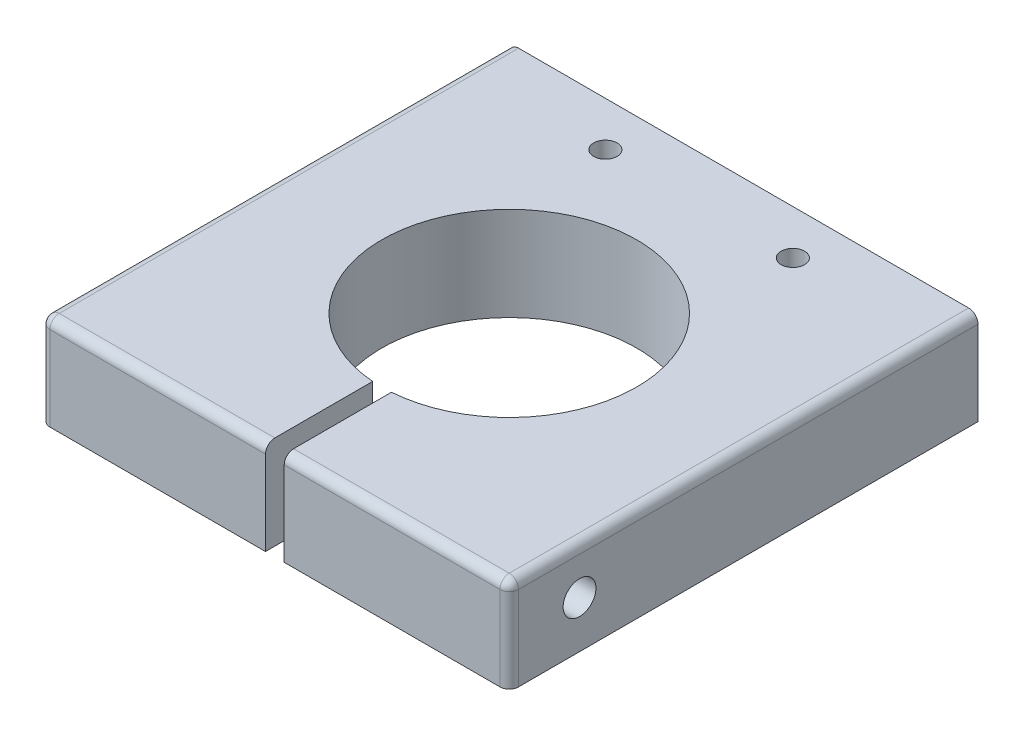
SolidWorks part; units mm, degrees
ref_plane "Front Plane" through (0, 0, 0) normal (0, 0, 1) x (1, 0, 0)
ref_plane "Top Plane" through (0, 0, 0) normal (0, 1, 0) x (1, 0, 0)
ref_plane "Right Plane" through (0, 0, 0) normal (1, 0, 0) x (0, 0, -1)
sketch "Esquisse1" plane through (0, 0, 0) normal (0, 1, 0) x (1, 0, 0)
  line L0 (0, 0) -> (50, 0)
  line L1 (50, 0) -> (50, -100)
  line L2 (50, -100) -> (2, -100)
  line L3 (2, -100) -> (2, -50)
  line L4 (2, -50) -> (0, -50)
  line L5 (0, -50) -> (0, 0)
  line L6 (0, 5.5872) -> (0, -102.666) construction
  dimension "D1" = 50
  dimension "D2" = 100
  dimension "D3" = 48
  dimension "D4" = 50
extrude "Boss.-Extru.1" add sketch "Esquisse1" along normal blind 20
mirror "Symétrie1" about plane through (0, 0, 0) normal (1, 0, 0) of "Boss.-Extru.1"
sketch "Esquisse2" plane through (0, 20, 0) normal (0, 1, 0) x (1, 0, 0)
  line L0 (-2, -50) -> (2, -50) construction
  circle A0 centre (0, -50) radius 27.2
extrude "Enlèv. mat.-Extru.1" cut sketch "Esquisse2" against normal blind 20
sketch "Esquisse3" plane through (0, 20, 0) normal (0, 1, 0) x (1, 0, 0)
  line L0 (0, -22.8) -> (0, 0) construction
  line L1 (50, 0) -> (-50, 0) construction
  circle A0 centre (20, -9.5) radius 2.5
  arc A1 (2, -77.1264) -> (-2, -77.1264) centre (0, -50) ccw construction
  dimension "D1" = 20
  dimension "D2" = 9.5
extrude "Enlèv. mat.-Extru.2" cut sketch "Esquisse3" against normal blind 20
mirror "Symétrie3" about plane through (0, 0, 0) normal (1, 0, 0) of "Enlèv. mat.-Extru.2"
sketch "Esquisse4" plane through (50, 0, 0) normal (1, 0, 0) x (0, 0, -1)
  line L0 (-100, 10) -> (0, 10) construction
  line L1 (-100, 20) -> (-100, 0) construction
  line L2 (0, 20) -> (0, 0) construction
  circle A0 centre (-85, 10) radius 3.5
  point P8 (0, 0)
  dimension "D1" = 15
extrude "Enlèv. mat.-Extru.3" cut sketch "Esquisse4" against normal through all
fillet "Congé1" radius 2 6 edges at (50, 10, 100) (-50, 10, 100) (50, 20, 50) (26, 20, 100) (-50, 20, 50) (-26, 20, 100)
